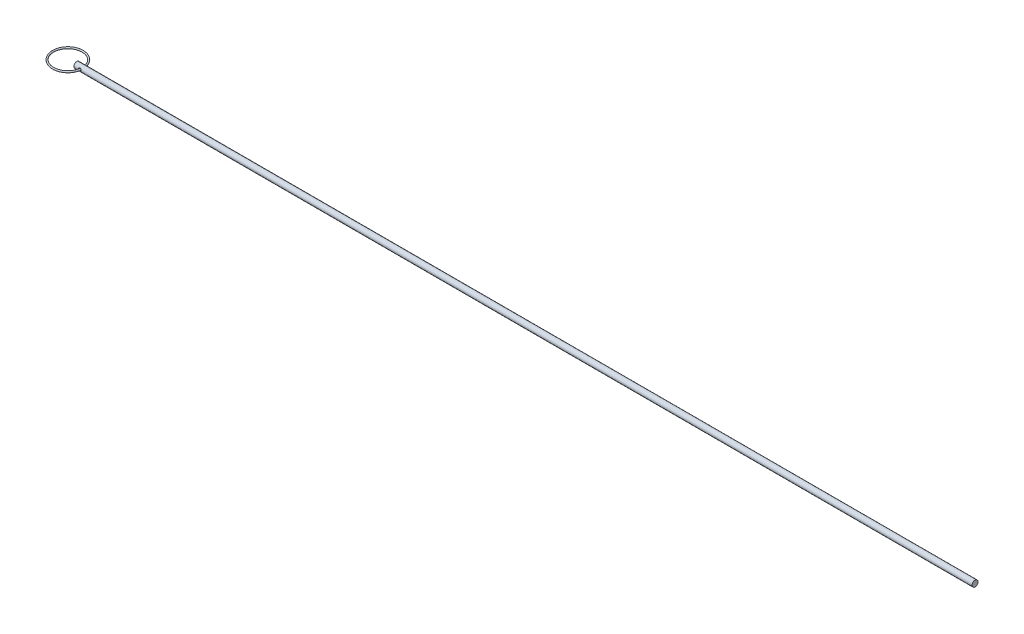
SolidWorks part; units mm, degrees
ref_plane "Front Plane" through (0, 0, 0) normal (0, 0, 1) x (1, 0, 0)
ref_plane "Top Plane" through (0, 0, 0) normal (0, 1, 0) x (1, 0, 0)
ref_plane "Right Plane" through (0, 0, 0) normal (1, 0, 0) x (0, 0, -1)
sketch "Sketch1" plane through (0, 0, 0) normal (1, 0, 0) x (0, 0, -1)
  circle A0 centre (0, 0) radius 0.5
  dimension "D1" = 1
extrude "Boss-Extrude1" add sketch "Sketch1" along normal blind 152.4
sketch "Sketch2" plane through (0, 0, 0) normal (0, 0, 1) x (1, 0, 0)
  line L0 (0, 0.5) -> (0, -0.5) construction
  circle A0 centre (1, 0) radius 0.25
  dimension "D1" = 0.5
  dimension "D2" = 1
extrude "Cut-Extrude1" cut sketch "Sketch2" against normal through all both and the other way through all
sketch "Sketch7" plane through (0, 0, 0) normal (0, 0, 1) x (1, 0, 0)
  line L0 (-1.5, 0.694) -> (-1.5, -0.7558)
  circle A0 centre (1, 0) radius 0.127
  dimension "D2" = 0.254
  dimension "D1" = 2.5
revolve "Revolve7" add sketch "Sketch7" angle 360 about L0
